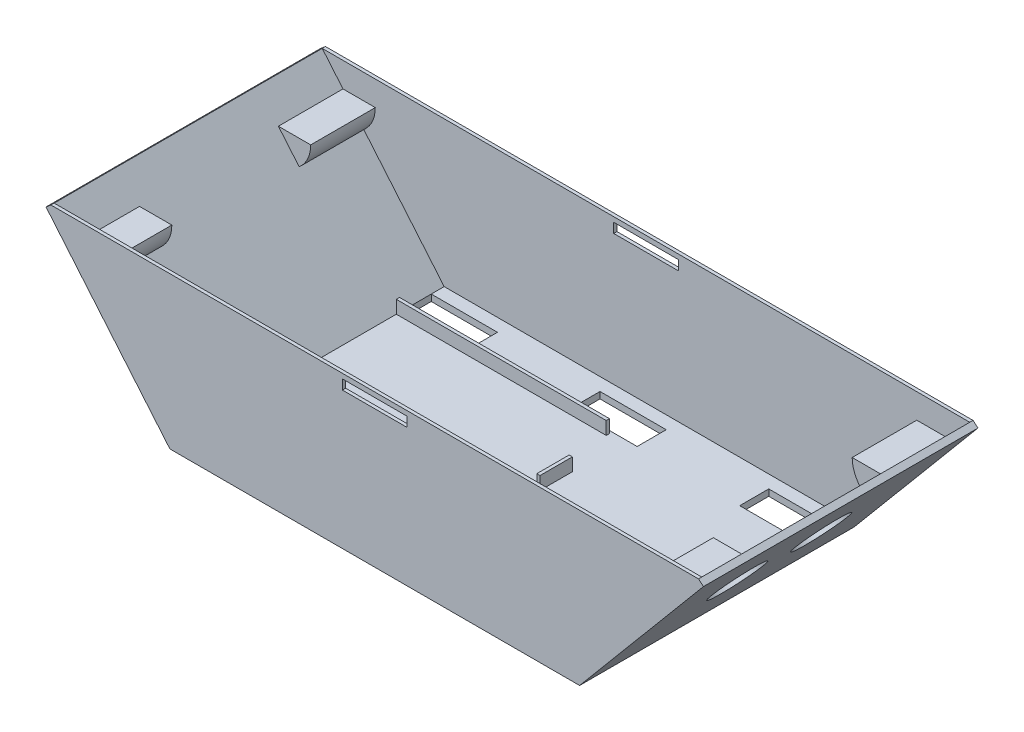
SolidWorks part; units mm, degrees
ref_plane "Plan de face" through (0, 0, 0) normal (0, 0, 1) x (1, 0, 0)
ref_plane "Plan de dessus" through (0, 0, 0) normal (0, 1, 0) x (1, 0, 0)
ref_plane "Plan de droite" through (0, 0, 0) normal (1, 0, 0) x (0, 0, -1)
sketch "Esquisse3" plane through (0, 0, 0) normal (0, 0, 1) x (1, 0, 0)
  line L0 (0, 0) -> (125, 0)
  line L1 (125, 0) -> (162.7595, 45)
  line L3 (-37.7595, 45) -> (0, 0)
  dimension "D1" = 130
  dimension "D2" = 125
  dimension "D3" = 45
  dimension "D4" = 130
extrude "Extru.-Mince1" add sketch "Esquisse3" along normal blind 85 thin
sketch "Esquisse5" plane through (0, 0, 0) normal (0, 0, -1) x (-1, 0, 0)
  line L0 (-162.7595, 45) -> (37.7595, 45)
  line L1 (-162.7595, 45) -> (-125, 0)
  line L2 (-125, 0) -> (0, 0)
  line L3 (0, 0) -> (37.7595, 45)
extrude "Boss.-Extru.1" add sketch "Esquisse5" against normal blind 1
sketch "Esquisse6" plane through (0, 0, 85) normal (0, 0, 1) x (1, 0, 0)
  line L0 (162.7595, 45) -> (-37.7595, 45)
  line L1 (-37.7595, 45) -> (0, 0)
  line L2 (0, 0) -> (125, 0)
  line L3 (125, 0) -> (162.7595, 45)
extrude "Boss.-Extru.2" add sketch "Esquisse6" against normal blind 1
sketch "Esquisse7" plane through (0, 0, 0) normal (0.766, 0.6428, 0) x (0, 0, -1)
  line L0 (-1, 48.7433) -> (-21, 48.7433)
  line L1 (-1, 0) -> (-1, 58.7433) construction
  line L2 (-84, 48.7433) -> (-64, 48.7433)
  line L3 (-84, 58.7433) -> (-84, 0) construction
  line L4 (-84, 58.7433) -> (-1, 58.7433) construction
  dimension "D1" = 20
  dimension "D2" = 20
  dimension "D3" = 10
revolve "Révol.-Mince1" add sketch "Esquisse7" angle 50 about L2
sketch "Esquisse8" plane through (0, 0, 0) normal (0.766, 0.6428, 0) x (0, 0, -1)
  line L0 (-1, 48.7433) -> (-21, 48.7433)
  line L1 (-1, 0) -> (-1, 58.7433) construction
  line L2 (-84, 58.7433) -> (-1, 58.7433) construction
  dimension "D1" = 10
  dimension "D2" = 20
revolve "Révol.-Mince2" add sketch "Esquisse8" angle 50 about L0 wall 10
sketch "Esquisse9" plane through (73.353, -61.5505, 0) normal (-0.766, 0.6428, 0) x (0, 0, 1)
  line L0 (84, 129.0918) -> (64, 129.0918)
  line L1 (84, 80.3485) -> (84, 139.0918) construction
  line L2 (84, 139.0918) -> (1, 139.0918) construction
  dimension "D1" = 20
  dimension "D2" = 10
revolve "Révol.-Mince3" add sketch "Esquisse9" angle 50 about L0 wall 10
sketch "Esquisse10" plane through (73.353, -61.5505, 0) normal (-0.766, 0.6428, 0) x (0, 0, 1)
  line L0 (1, 129.0918) -> (21, 129.0918)
  line L1 (1, 139.0918) -> (1, 80.3485) construction
  line L2 (84, 139.0918) -> (1, 139.0918) construction
  dimension "D1" = 20
  dimension "D2" = 10
revolve "Révol.-Mince4" add sketch "Esquisse10" angle 50 about L0
sketch "Esquisse12" plane through (0, 0, 0) normal (0, 1, 0) x (1, 0, 0)
  line L0 (0, -84) -> (0, -1) construction
  line L1 (0, -5) -> (20.5, -5)
  line L2 (0, -5) -> (0, -14)
  line L3 (0, -14) -> (20.5, -14)
  line L4 (20.5, -5) -> (20.5, -14)
  line L5 (125, -1) -> (0, -1) construction
  line L6 (0, -84) -> (125, -84) construction
  line L7 (0, -71) -> (20.5, -71)
  line L8 (0, -71) -> (0, -80)
  line L9 (0, -80) -> (20.5, -80)
  line L10 (20.5, -71) -> (20.5, -80)
  line L11 (125, -84) -> (125, -1) construction
  line L12 (125, -14) -> (104.5, -14)
  line L13 (125, -14) -> (125, -5)
  line L14 (125, -5) -> (104.5, -5)
  line L15 (104.5, -14) -> (104.5, -5)
  line L17 (125, -80) -> (104.5, -80)
  line L18 (125, -80) -> (125, -71)
  line L19 (125, -71) -> (104.5, -71)
  line L20 (104.5, -80) -> (104.5, -71)
  dimension "D1" = 20.5
  dimension "D2" = 9
  dimension "D3" = 4
  dimension "D4" = 9
  dimension "D5" = 4
  dimension "D6" = 20.5
  dimension "D7" = 4
  dimension "D8" = 9
  dimension "D9" = 4
  dimension "D10" = 20.5
  dimension "D11" = 20.5
extrude "Enlèv. mat.-Extru.2" cut sketch "Esquisse12" against normal blind 10
sketch "Esquisse13" plane through (0, 0, 0) normal (0, 1, 0) x (1, 0, 0)
  line L0 (0, -84) -> (125, -84) construction
  line L1 (52.25, -5) -> (72.75, -5)
  line L2 (52.25, -5) -> (52.25, -14)
  line L3 (52.25, -14) -> (72.75, -14)
  line L4 (72.75, -5) -> (72.75, -14)
  line L5 (52.25, -80) -> (72.75, -80)
  line L6 (52.25, -80) -> (52.25, -71)
  line L7 (52.25, -71) -> (72.75, -71)
  line L8 (72.75, -80) -> (72.75, -71)
  line L9 (125, -1) -> (0, -1) construction
  line L10 (20.5, -14) -> (20.5, -5) construction
  line L13 (20.5, -80) -> (20.5, -71) construction
  point P14 (52.25, -9.5)
  point P19 (52.25, -75.5)
  dimension "D1" = 4
  dimension "D2" = 20.5
  dimension "D3" = 9
  dimension "D4" = 4
  dimension "D5" = 20.5
  dimension "D6" = 9
  dimension "D7" = 31.75
  dimension "D8" = 31.75
extrude "Enlèv. mat.-Extru.3" cut sketch "Esquisse13" against normal blind 10
sketch "Esquisse14" plane through (0, 0, 0) normal (0, 1, 0) x (1, 0, 0)
  line L0 (0, -14.8197) -> (65, -14.8197)
  line L1 (0, -71) -> (0, -14) construction
  line L2 (0, -68.3197) -> (65, -68.3197)
  dimension "D1" = 65
  dimension "D2" = 65
  dimension "D3" = 53.5
extrude "Extru.-Mince2" add sketch "Esquisse14" along normal blind 4 thin
sketch "Esquisse15" plane through (0, 0, 0) normal (0, 1, 0) x (1, 0, 0)
  line L0 (68.5, -30.8197) -> (68.5, -40.8197)
  line L1 (0, -68.3197) -> (0, -15.8197) construction
  dimension "D1" = 68.5
  dimension "D2" = 10
  dimension "D3" = 15
extrude "Extru.-Mince3" add sketch "Esquisse15" along normal blind 4 thin thin type one direction reverse wall 1
sketch "Esquisse16" plane through (0, 0, 1) normal (0, 0, 1) x (1, 0, 0)
  line L0 (-21.3316, 37.3396) -> (146.3316, 37.3396) construction
  line L1 (62.5, 45) -> (62.5, 0) construction
  line L2 (-37.7595, 45) -> (162.7595, 45) construction
  line L3 (125, 0) -> (0, 0) construction
  line L5 (52.5, 43.5) -> (72.5, 43.5)
  line L6 (52.5, 43.5) -> (52.5, 40.5)
  line L7 (52.5, 40.5) -> (72.5, 40.5)
  line L8 (72.5, 43.5) -> (72.5, 40.5)
  line L9 (52.5, 43.5) -> (72.5, 40.5) construction
  line L10 (52.5, 40.5) -> (72.5, 43.5) construction
  point P10 (62.5, 42)
  dimension "D1" = 3
  dimension "D2" = 20
  dimension "D3" = 1.5
extrude "Enlèv. mat.-Extru.4" cut sketch "Esquisse16" against normal blind 10
sketch "Esquisse17" plane through (0, 0, 84) normal (0, 0, -1) x (-1, 0, 0)
  line L0 (-146.3316, 37.3396) -> (21.3316, 37.3396) construction
  line L1 (-62.5, 0) -> (-62.5, 45) construction
  line L2 (0, 0) -> (-125, 0) construction
  line L3 (-162.7595, 45) -> (37.7595, 45) construction
  line L5 (-72.5, 40.5) -> (-52.5, 40.5)
  line L6 (-72.5, 40.5) -> (-72.5, 43.5)
  line L7 (-72.5, 43.5) -> (-52.5, 43.5)
  line L8 (-52.5, 40.5) -> (-52.5, 43.5)
  line L9 (-72.5, 40.5) -> (-52.5, 43.5) construction
  line L10 (-72.5, 43.5) -> (-52.5, 40.5) construction
  point P10 (-62.5, 42)
  dimension "D1" = 20
  dimension "D2" = 3
  dimension "D3" = 1.5
extrude "Enlèv. mat.-Extru.5" cut sketch "Esquisse17" against normal blind 10
sketch "Esquisse19" plane through (74.8851, -62.8361, 0) normal (0.766, -0.6428, 0) x (0, 0, -1)
  line L0 (-85, 79.4158) -> (0, 79.4158) construction
  circle A0 centre (-29.5, 109.4158) radius 8.005
  circle A1 centre (-55.5, 109.4158) radius 8.005
  dimension "D5" = 16.01
  dimension "D6" = 16.01
  dimension "D1" = 29.5
  dimension "D2" = 29.5
  dimension "D3" = 30
  dimension "D4" = 30
extrude "Enlèv. mat.-Extru.6" cut sketch "Esquisse19" against normal blind 10
